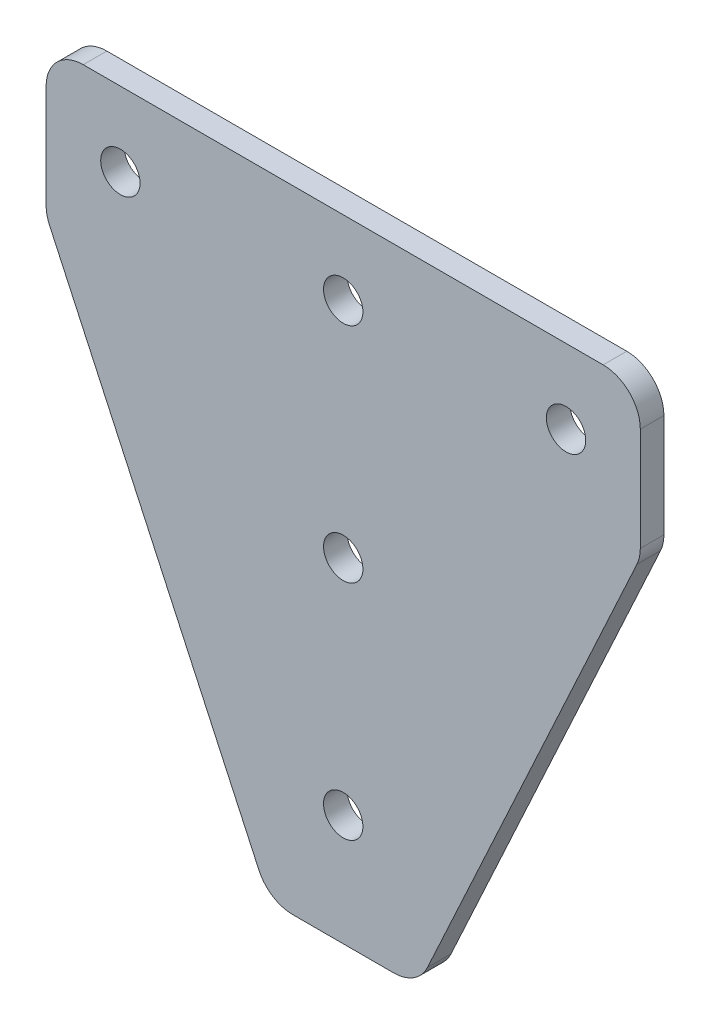
SolidWorks part; units mm, degrees
ref_plane "Front Plane" through (0, 0, 0) normal (0, 0, 1) x (1, 0, 0)
ref_plane "Top Plane" through (0, 0, 0) normal (0, 1, 0) x (1, 0, 0)
ref_plane "Right Plane" through (0, 0, 0) normal (1, 0, 0) x (0, 0, -1)
sketch "Sketch1" plane through (0, 0, 0) normal (0, 0, 1) x (1, 0, 0)
  line L0 (0, 0) -> (0, -85) construction
  line L1 (-10, -85) -> (10, -85)
  line L2 (10, -85) -> (40, -20)
  line L3 (40, -20) -> (40, 0)
  line L4 (40, 0) -> (-40, 0)
  line L5 (-40, -20) -> (-40, 0)
  line L6 (-10, -85) -> (-40, -20)
  dimension "D1" = 40
  dimension "D2" = 20
  dimension "D3" = 85
extrude "Boss-Extrude1" add sketch "Sketch1" along normal blind 3.175
sketch "Sketch2" plane through (0, 0, 3.175) normal (0, 0, 1) x (1, 0, 0)
  line L0 (0, -10) -> (40, -10) construction
  line L2 (40, -20) -> (40, 0) construction
  line L3 (0, 0) -> (0, -85) construction
  line L4 (40, 0) -> (-40, 0) construction
  line L5 (-10, -85) -> (10, -85) construction
  circle A0 centre (0, -10) radius 2.65
  circle A1 centre (30, -10) radius 2.65
  circle A3 centre (0, -40) radius 2.65
  circle A4 centre (0, -70) radius 2.65
  circle A5 centre (-30, -10) radius 2.65
  dimension "D3" = 5.3
  dimension "D4" = 30
  dimension "D6" = 30
  dimension "D1" = 10
  dimension "D5" = 30
extrude "Cut-Extrude1" cut sketch "Sketch2" against normal through all
fillet "Fillet1" radius 5 6 edges at (40, -20, 1.5875) (10, -85, 1.5875) (40, 0, 1.5875) (-40, -20, 1.5875) (-10, -85, 1.5875) (-40, 0, 1.5875)
